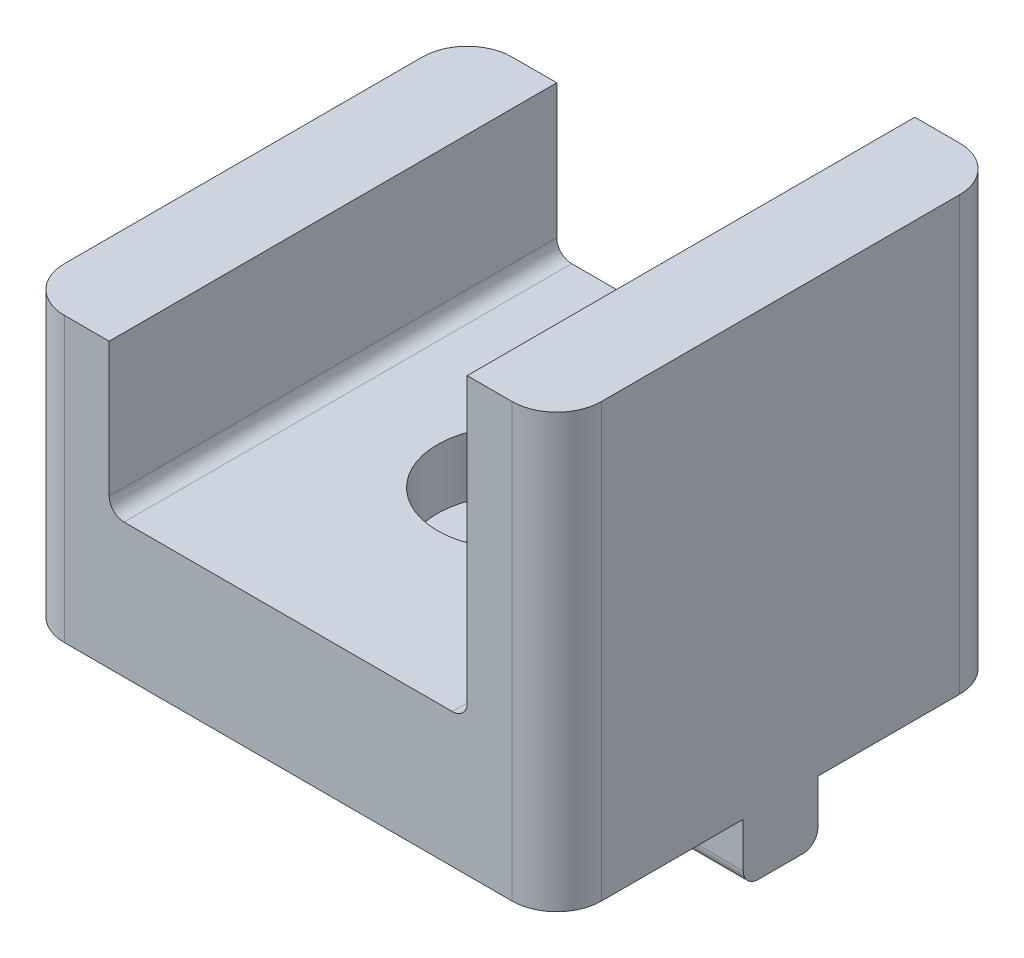
SolidWorks part; units mm, degrees
ref_plane "Front Plane" through (0, 0, 0) normal (0, 0, 1) x (1, 0, 0)
ref_plane "Top Plane" through (0, 0, 0) normal (0, 1, 0) x (1, 0, 0)
ref_plane "Right Plane" through (0, 0, 0) normal (1, 0, 0) x (0, 0, -1)
sketch "Sketch1" plane through (0, 0, 0) normal (0, 0, 1) x (1, 0, 0)
  line L0 (0, -55) -> (0, 55) construction
  line L1 (12, -4.5) -> (-12, -4.5)
  line L2 (12, -4.5) -> (12, 4.5)
  line L3 (12, 4.5) -> (-12, 4.5)
  line L4 (-12, -4.5) -> (-12, 4.5)
  line L5 (12, -4.5) -> (-12, 4.5) construction
  line L6 (12, 4.5) -> (-12, -4.5) construction
  line L7 (-12, -4.5) -> (-18, -4.5)
  line L8 (-12, -4.5) -> (-12, 14.5)
  line L9 (-12, 14.5) -> (-18, 14.5)
  line L10 (-18, -4.5) -> (-18, 14.5)
  line L15 (12, -4.5) -> (12, 4.5)
  line L17 (12, -4.5) -> (18, -4.5)
  line L18 (12, -4.5) -> (12, 24.5)
  line L19 (12, 24.5) -> (18, 24.5)
  line L20 (18, -4.5) -> (18, 24.5)
  point P0 (0, 0)
  dimension "D1" = 24
  dimension "D2" = 6
  dimension "D3" = 9
  dimension "D4" = 19
  dimension "D5" = 6
  dimension "D6" = 29
extrude "Boss-Extrude1" add sketch "Sketch1" along normal blind 30 contours L10 L7 L4 L8 L9 | L4 L1 L2 L3 | L17 L20 L19 L18 L2
fillet "Fillet1" radius 1 2 edges at (12, 4.5, 15) (-12, 4.5, 15)
fillet "Fillet2" radius 3 4 edges at (18, 10, 0) (18, 10, 30) (-18, 5, 0) (-18, 5, 30)
sketch "Sketch3" plane through (0, 4.5, 0) normal (0, 1, 0) x (1, 0, 0)
  line L0 (11, -30) -> (11, 0) construction
  circle A1 centre (0, -15) radius 2.5
  point P2 (11, -15)
  dimension "D1" = 0
extrude "Cut-Extrude2" cut sketch "Sketch3" against normal blind 10
sketch "Sketch4" plane through (0, 4.5, 0) normal (0, 1, 0) x (1, 0, 0)
  circle A0 centre (0, -15) radius 5
extrude "Cut-Extrude3" cut sketch "Sketch4" against normal blind 4
sketch "Sketch5" plane through (0, -4.5, 0) normal (0, -1, 0) x (1, 0, 0)
  line L0 (-18, 27) -> (-18, 3) construction
  line L1 (-18, 17.5) -> (-10, 17.5)
  line L2 (-18, 17.5) -> (-18, 12.5)
  line L3 (-18, 12.5) -> (-10, 12.5)
  line L4 (-10, 17.5) -> (-10, 12.5)
  line L5 (18, 27) -> (18, 3) construction
  line L6 (18, 17.5) -> (10, 17.5)
  line L7 (18, 17.5) -> (18, 12.5)
  line L8 (18, 12.5) -> (10, 12.5)
  line L9 (10, 17.5) -> (10, 12.5)
  dimension "D1" = 8
  dimension "D2" = 8
extrude "Boss-Extrude2" add sketch "Sketch5" along normal blind 4
fillet "Fillet3" radius 1 4 edges at (14, -8.5, 12.5) (14, -8.5, 17.5) (-14, -8.5, 12.5) (-14, -8.5, 17.5)
